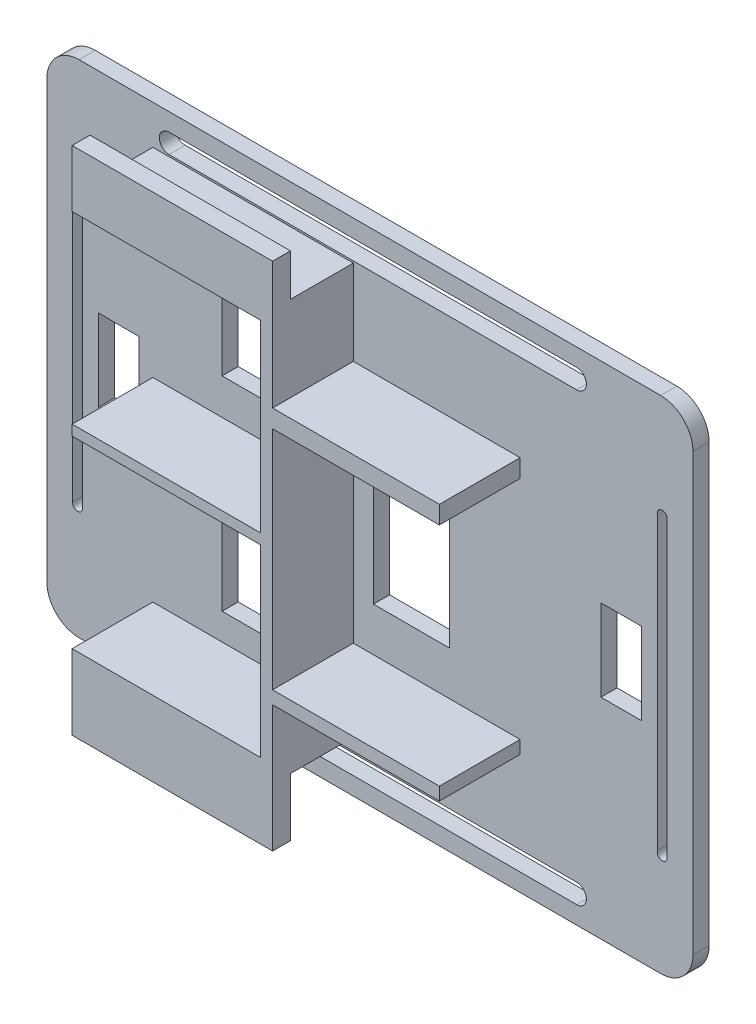
SolidWorks part; units mm, degrees
material "Aleación 1060"
ref_plane "Alzado" through (0, 0, 0) normal (0, 0, 1) x (1, 0, 0)
ref_plane "Planta" through (0, 0, 0) normal (0, 1, 0) x (1, 0, 0)
ref_plane "Vista lateral" through (0, 0, 0) normal (1, 0, 0) x (0, 0, -1)
sketch "Croquis2" plane through (0, 0, 0) normal (0, 0, 1) x (1, 0, 0)
  line L0 (64.1083, -69.4434) -> (64.1083, -63.7587) construction
  line L1 (-99.8917, -77.9434) -> (100.1083, -77.9434)
  line L2 (-99.8917, -77.9434) -> (-99.8917, 77.0566)
  line L3 (-99.8917, 77.0566) -> (100.1083, 77.0566)
  line L4 (100.1083, -77.9434) -> (100.1083, 77.0566)
  line L6 (100.1083, -69.4434) -> (-31.2492, -69.4434) construction
  line L7 (-32.0917, -69.4434) -> (-32.0917, -66.4434) construction
  line L8 (-62.0917, -69.4434) -> (-62.0917, -66.4434) construction
  line L11 (0.1083, -66.4434) -> (0.1083, -77.9434) construction
  line L15 (71.6083, -0.4434) -> (100.1083, -0.4434) construction
  line L28 (0, 0) -> (0, 65.5566) construction
  line L34 (-99.8917, -0.4434) -> (-71.3917, -0.4434) construction
  line L35 (-62.0917, 71.5566) -> (64.1083, 71.5566)
  line L38 (-71.3917, -12.9858) -> (-71.3917, 12.099)
  line L41 (-79.2417, -13.0101) -> (-71.3917, -12.9858)
  line L45 (92.1083, 45.395) -> (92.1083, -46.2819)
  line L46 (89.1083, 44.5566) -> (89.1083, -45.4434)
  line L47 (84.1083, 12.2066) -> (84.1083, -13.0934)
  line L48 (84.1083, -13.0934) -> (79.4583, -13.0934)
  line L49 (71.6083, -13.0934) -> (71.6083, 12.2066)
  line L52 (79.4583, -13.0934) -> (71.6083, -13.0934)
  line L53 (84.1083, 12.2066) -> (79.4583, 12.2066)
  line L69 (-83.8917, -13.0934) -> (-79.2417, -13.0101)
  line L70 (-83.8917, 12.2066) -> (-83.8917, -13.0934)
  line L71 (-91.8917, 41.6585) -> (-91.8917, -42.5454)
  line L72 (-88.8917, 42.0566) -> (-88.8917, -42.9434)
  line L82 (79.4583, 12.2066) -> (71.6083, 12.2066)
  line L85 (-79.2417, 12.1233) -> (-71.3917, 12.099)
  line L86 (-83.8917, 12.2066) -> (-79.2417, 12.1233)
  line L99 (-45.6601, 58.1834) -> (-14.3628, 58.1834)
  line L102 (64.1083, 65.5566) -> (-62.0917, 65.5566)
  line L103 (-62.0917, -72.4434) -> (64.1083, -72.4434)
  line L104 (64.1083, -66.4434) -> (-62.0917, -66.4434)
  line L118 (-45.6601, 58.1834) -> (-45.6601, 14.4146)
  line L119 (-45.6601, 14.4146) -> (-14.3628, 14.4146)
  line L120 (-14.3628, 58.1834) -> (-14.3628, 14.4146)
  line L121 (-45.6601, -4.9147) -> (-14.3628, -4.9147)
  line L122 (-45.6601, -4.9147) -> (-45.6601, -48.6834)
  line L123 (-45.6601, -48.6834) -> (-14.3628, -48.6834)
  line L124 (-14.3628, -4.9147) -> (-14.3628, -48.6834)
  line L125 (1.1959, 21.9686) -> (24.7698, 21.9686)
  line L126 (1.1959, 21.9686) -> (1.1959, -23.3553)
  line L127 (1.1959, -23.3553) -> (24.7698, -23.3553)
  line L128 (24.7698, 21.9686) -> (24.7698, -23.3553)
  arc A1 (64.1083, -72.4434) -> (64.1083, -66.4434) centre (64.1083, -69.4434) ccw
  arc A6 (-62.0917, -66.4434) -> (-62.0917, -72.4434) centre (-62.0917, -69.4434) ccw
  arc A92 (89.1083, -45.4434) -> (92.1083, -46.2819) centre (90.6083, -45.8626) ccw
  arc A97 (-88.8917, -42.9434) -> (-91.8917, -42.5454) centre (-90.3917, -42.7444) cw
  arc A108 (-88.8917, 42.0566) -> (-91.8917, 41.6585) centre (-90.3917, 41.8576) ccw
  arc A109 (89.1083, 44.5566) -> (92.1083, 45.395) centre (90.6083, 44.9758) cw
  arc A113 (64.1083, 71.5566) -> (64.1083, 65.5566) centre (64.1083, 68.5566) cw
  arc A146 (-62.0917, 65.5566) -> (-62.0917, 71.5566) centre (-62.0917, 68.5566) cw
  point P0 (0, 0)
  point P58 (0, 0)
  point P78 (3.0535, -59.0858)
  point P80 (1.1959, -58.7698)
  point P84 (89.4782, -52.7527)
  point P89 (81.5012, -58.7833)
  point P95 (-80.8654, -59.4434)
  point P116 (-91.8917, -0.4434)
  point P120 (-5.0314, -61.027)
  point P121 (11.1384, -58.7698)
  point P128 (84.1083, -0.4434)
  point P135 (71.6083, -0.4434)
  point P139 (-71.3917, -0.4434)
  point P140 (-83.8917, -0.4434)
  point P143 (-88.8917, -0.4434)
  point P144 (0.0463, 58.5996)
  point P149 (89.1083, -0.4434)
  point P150 (92.1083, -0.4434)
  point P155 (81.5012, 58.0631)
  point P171 (49.6083, -0.4434)
  point P173 (46.6083, -0.4434)
  point P228 (1.1959, 58.2649)
  point P247 (7.6372, -0.4434)
  point P258 (-14.3628, -0.4434)
  point P290 (-80.8654, 58.38)
  dimension "D14" = 5.5
  dimension "D17" = 43.7687
  dimension "D18" = 45.324
  dimension "D20" = 3
  dimension "D32" = 8
  dimension "D1" = 200
  dimension "D16" = 43.7687
  dimension "D35" = 12.65
  dimension "D36" = 5
  dimension "D42" = 4.65
  dimension "D43" = 12.5
extrude "Saliente-Extruir1" add sketch "Croquis2" along normal blind 5
fillet "Redondeo1" radius 10 4 edges at (-99.8917, 77.0566, 2.5) (-99.8917, -77.9434, 2.5) (100.1083, -77.9434, 2.5) (100.1083, 77.0566, 2.5)
sketch "Sketch1" plane through (0, 0, 5) normal (0, 0, 1) x (1, 0, 0)
  line L0 (-67.0718, 64.9767) -> (-67.0718, 60.278)
  line L1 (-67.0718, 60.278) -> (-8.8412, 60.278)
  line L2 (-8.8412, 60.278) -> (-8.8412, 3.278)
  line L3 (-8.8412, 3.278) -> (-67.0718, 3.278)
  line L4 (-67.0718, 3.278) -> (-67.0718, 0.0701)
  line L5 (-67.0718, 0.0701) -> (-8.8412, 0.0701)
  line L6 (-8.8412, 0.0701) -> (-8.8412, -56.9299)
  line L7 (-8.8412, -56.9299) -> (-67.0718, -56.9299)
  line L8 (-67.0718, -56.9299) -> (-67.0718, -62.1507)
  line L9 (-67.0718, -62.1507) -> (-5.0314, -62.1507)
  line L10 (-5.0314, -62.1507) -> (-5.0314, -40.9314)
  line L11 (-5.0314, -40.9314) -> (46.6083, -40.9314)
  line L12 (46.6083, -40.9314) -> (46.6083, -36.9314)
  line L13 (46.6083, -36.9314) -> (-5.0314, -36.9314)
  line L14 (-5.0314, -36.9314) -> (-5.0314, 33.0686)
  line L15 (-5.0314, 33.0686) -> (46.6083, 33.0686)
  line L16 (46.6083, 33.0686) -> (46.6083, 38.6115)
  line L17 (46.6083, 38.6115) -> (-5.0314, 38.6115)
  line L18 (-5.0314, 38.6115) -> (-5.0314, 64.9767)
  line L19 (-5.0314, 64.9767) -> (-67.0718, 64.9767)
  dimension "D1" = 70
  dimension "D2" = 57
  dimension "D3" = 57
extrude "Boss-Extrude1" add sketch "Sketch1" along normal blind 25
sketch "Sketch3" plane through (0, -62.1507, 0) normal (0, -1, 0) x (1, 0, 0)
  line L0 (-5.0314, 30) -> (-5.0314, 5) construction
  line L1 (-67.0718, 30) -> (-5.0314, 30)
  line L2 (-67.0718, 30) -> (-67.0718, 24.4692)
  line L3 (-67.0718, 24.4692) -> (-5.0314, 24.4692)
  line L4 (-5.0314, 30) -> (-5.0314, 24.4692)
  line L5 (-99.8917, 0) -> (-99.8917, 5) construction
  line L6 (-67.0718, 5) -> (-5.0314, 5) construction
  dimension "D1" = 32.8199
  dimension "D2" = 19.4692
  dimension "D3" = 62.0404
  dimension "D4" = 5.5308
extrude "Boss-Extrude2" add sketch "Sketch3" along normal blind 18
sketch "Sketch8" plane through (0, 64.9767, 0) normal (0, 1, 0) x (1, 0, 0)
  line L0 (-67.0718, -24.4692) -> (-5.0314, -24.4692)
  line L1 (-5.0314, -30) -> (-5.0314, -5) construction
  line L2 (-5.0314, -24.4692) -> (-5.0314, -30)
  line L3 (-5.0314, -30) -> (-67.0718, -30)
  line L4 (-67.0718, -30) -> (-67.0718, -24.4692)
extrude "Boss-Extrude6" add sketch "Sketch8" along normal blind 13
sketch "Sketch2" plane through (0, -77.9434, 0) normal (0, -1, 0) x (1, 0, 0)
  line L1 (-99.8917, 5) -> (100.1083, 5)
  line L2 (-99.8917, 5) -> (-99.8917, 80.1241)
  line L3 (-99.8917, 80.1241) -> (100.1083, 80.1241)
  line L4 (100.1083, 5) -> (100.1083, 80.1241)
  line L5 (-67.0718, 30) -> (-5.0314, 30)
  line L6 (-67.0718, 30) -> (-67.0718, 24.4692)
  line L7 (-67.0718, 24.4692) -> (-5.0314, 24.4692)
  line L8 (-5.0314, 30) -> (-5.0314, 24.4692)
